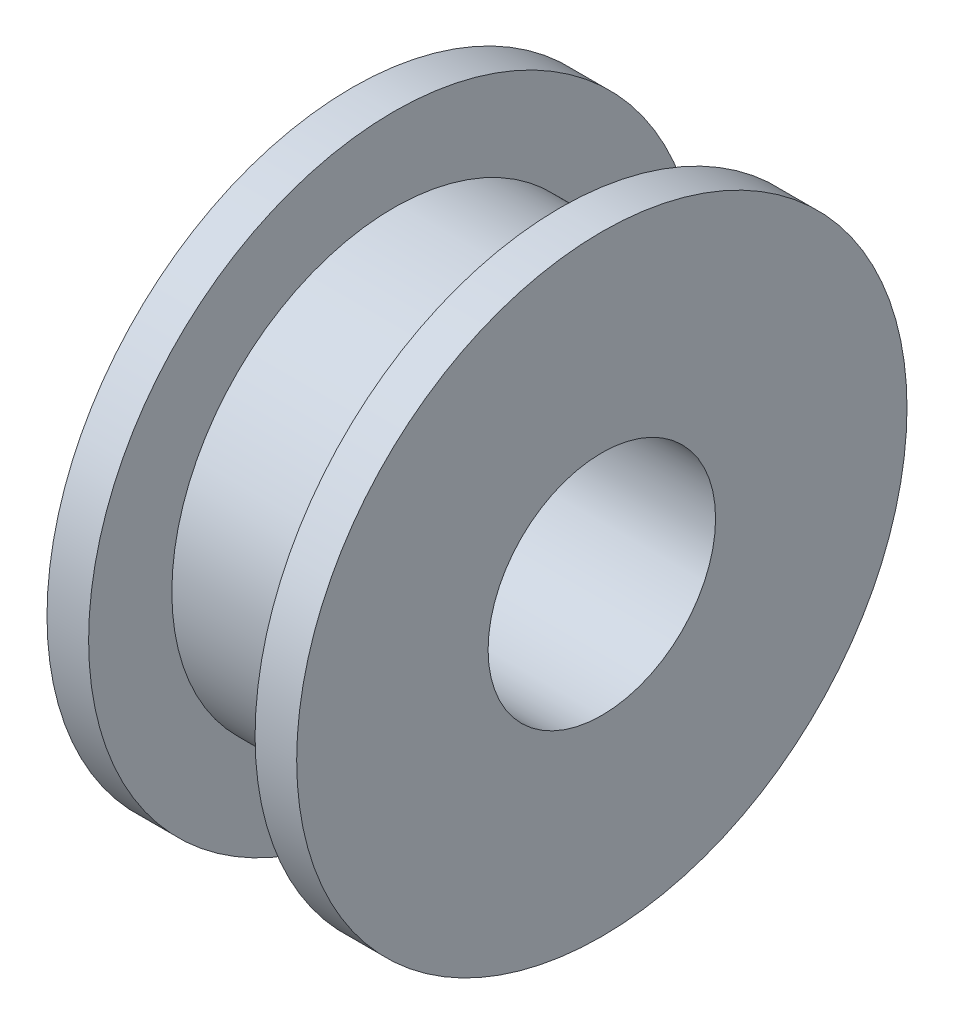
SolidWorks part; units mm, degrees
ref_plane "Front Plane" through (0, 0, 0) normal (0, 0, 1) x (1, 0, 0)
ref_plane "Top Plane" through (0, 0, 0) normal (0, 1, 0) x (1, 0, 0)
ref_plane "Right Plane" through (0, 0, 0) normal (1, 0, 0) x (0, 0, -1)
sketch "Sketch1" plane through (0, 0, 0) normal (0, 0, 1) x (1, 0, 0)
  line L0 (0, 0) -> (5.1881, 0) construction
  line L2 (-5.5, -0.875) -> (-5.5, 11) construction
  line L3 (-5.5, 11) -> (3.5, 11)
  line L4 (3.5, 4.1) -> (3.5, 11)
  line L5 (-5.5, 11) -> (-5.5, 4.1)
  line L8 (-5.5, 4.1) -> (3.5, 4.1)
  dimension "D1" = 11
  dimension "D2" = 9
  dimension "D5" = 4.1
revolve "Revolve1" add sketch "Sketch1" angle 360 about L0
sketch "Sketch2" plane through (0, 0, 0) normal (0, 0, 1) x (1, 0, 0)
  line L6 (0, 0) -> (5.4705, 0) construction
  line L9 (3.5, 3.3693) -> (3.5, 11) construction
  line L10 (3.5, 11) -> (2, 11) construction
  line L11 (2, 11) -> (2, 8) construction
  line L12 (2, 8) -> (-5.5, 8) construction
  line L13 (-5.5, 8) -> (-5.5, 3.3693) construction
  line L14 (3.5, 11) -> (-5.5, 11) construction
  line L15 (3.5, -11) -> (3.5, 11) construction
  line L16 (-5.5, 11) -> (-5.5, -11) construction
  line L17 (2, 8) -> (2, 11)
  line L18 (2, 11) -> (-4, 11)
  line L20 (-4, 11) -> (-4, 8)
  line L21 (-4, 8) -> (2, 8)
  dimension "D1" = 3
  dimension "D2" = 1.5
  dimension "D3" = 1.5
revolve "Cut-Revolve1" cut sketch "Sketch2" angle 360 about L6
